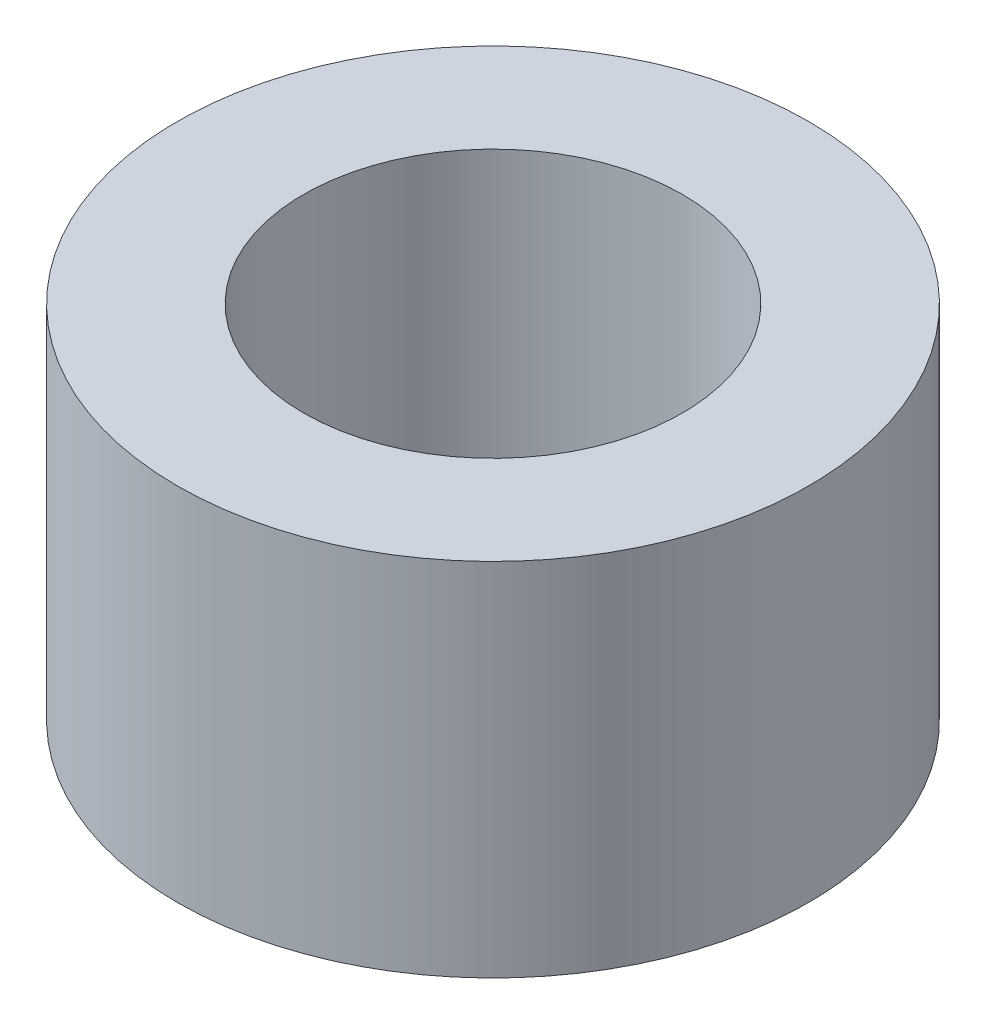
SolidWorks part; units mm, degrees
material "ABS"
ref_plane "前视基准面" through (0, 0, 0) normal (0, 0, 1) x (1, 0, 0)
ref_plane "上视基准面" through (0, 0, 0) normal (0, 1, 0) x (1, 0, 0)
ref_plane "右视基准面" through (0, 0, 0) normal (1, 0, 0) x (0, 0, -1)
sketch "草图1" plane through (0, 0, 0) normal (0, 1, 0) x (1, 0, 0)
  circle A0 centre (0, 0) radius 2.1
  circle A1 centre (0, 0) radius 3.5
  dimension "D1" = 7
  dimension "D2" = 4.2
extrude "凸台-拉伸1" add sketch "草图1" along normal blind 4
